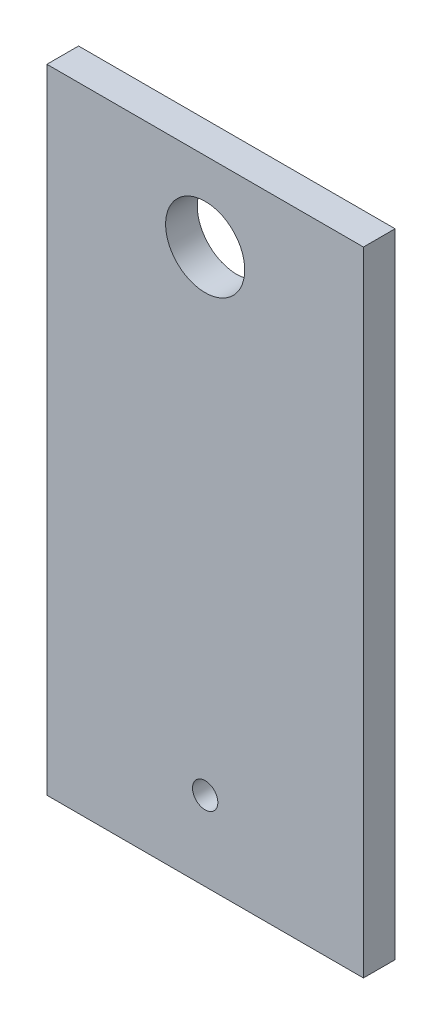
SolidWorks part; units mm, degrees
ref_plane "Front Plane" through (0, 0, 0) normal (0, 0, 1) x (1, 0, 0)
ref_plane "Top Plane" through (0, 0, 0) normal (0, 1, 0) x (1, 0, 0)
ref_plane "Right Plane" through (0, 0, 0) normal (1, 0, 0) x (0, 0, -1)
sketch "Sketch1" plane through (0, 0, 0) normal (0, 0, 1) x (1, 0, 0)
  line L1 (-50, 100) -> (50, 100)
  line L2 (-50, 100) -> (-50, -100)
  line L3 (-50, -100) -> (50, -100)
  line L4 (50, 100) -> (50, -100)
  line L5 (-50, 100) -> (50, -100) construction
  line L6 (-50, -100) -> (50, 100) construction
  point P0 (0, 0)
  dimension "D1" = 200
  dimension "D2" = 100
extrude "Boss-Extrude1" add sketch "Sketch1" along normal blind 10
sketch "Sketch3" plane through (0, 0, 10) normal (0, 0, 1) x (1, 0, 0)
  line L0 (0, -100) -> (0, -75) construction
  line L1 (-50, -100) -> (50, -100) construction
  circle A0 centre (0, -75) radius 4
  dimension "D1" = 25
extrude "Cut-Extrude2" cut sketch "Sketch3" against normal through all
sketch "Sketch4" plane through (0, 0, 10) normal (0, 0, 1) x (1, 0, 0)
  line L0 (0, 100) -> (0, 75) construction
  line L1 (50, 100) -> (-50, 100) construction
  circle A0 centre (0, 75) radius 4
  dimension "D1" = 25
extrude "Cut-Extrude3" cut sketch "Sketch4" against normal through all
sketch "Sketch5" plane through (0, 0, 10) normal (0, 0, 1) x (1, 0, 0)
  circle A0 centre (0, 75) radius 12.5
extrude "Cut-Extrude4" cut sketch "Sketch5" against normal through all
